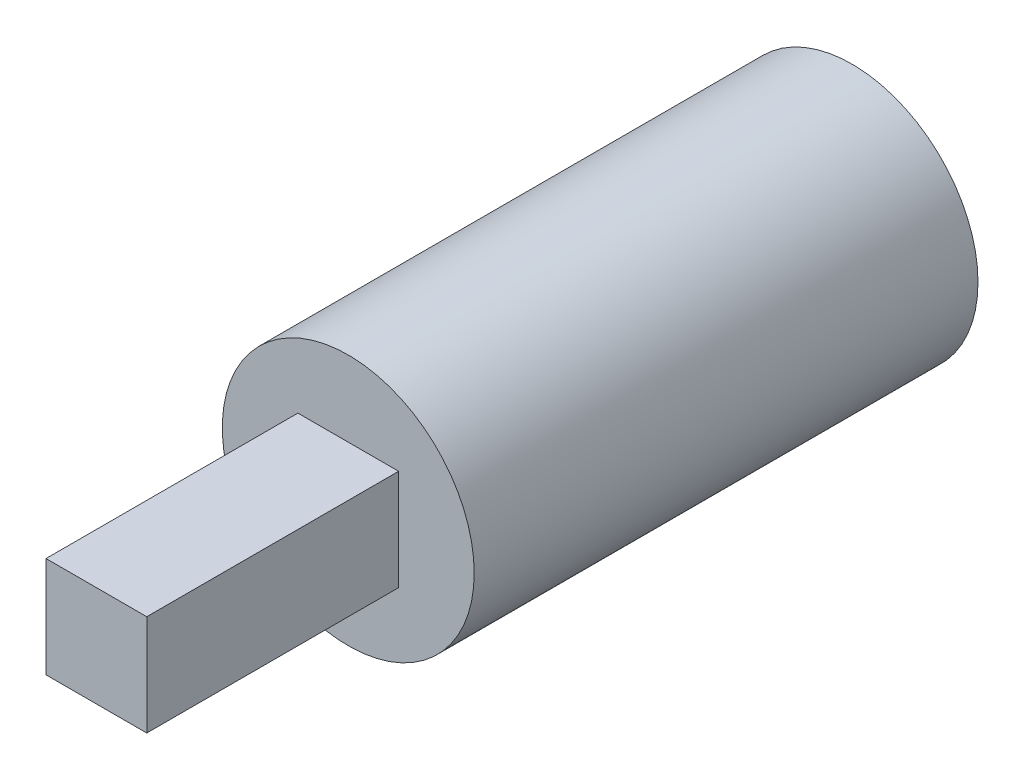
SolidWorks part; units mm, degrees
ref_plane "前视基准面" through (0, 0, 0) normal (0, 0, 1) x (1, 0, 0)
ref_plane "上视基准面" through (0, 0, 0) normal (0, 1, 0) x (1, 0, 0)
ref_plane "右视基准面" through (0, 0, 0) normal (1, 0, 0) x (0, 0, -1)
sketch "草图2" plane through (0, 0, 0) normal (0, 0, 1) x (1, 0, 0)
  circle A0 centre (0, 0) radius 2.5
  dimension "D1" = 5
extrude "凸台-拉伸1" add sketch "草图2" along normal blind 10
sketch "草图3" plane through (0, 0, 10) normal (0, 0, 1) x (1, 0, 0)
  line L1 (-1, -1) -> (1, -1)
  line L2 (-1, -1) -> (-1, 1)
  line L3 (-1, 1) -> (1, 1)
  line L4 (1, -1) -> (1, 1)
  line L5 (-1, -1) -> (1, 1) construction
  line L6 (-1, 1) -> (1, -1) construction
  point P0 (0, 0)
  dimension "D1" = 2
extrude "凸台-拉伸2" add sketch "草图3" along normal blind 5
